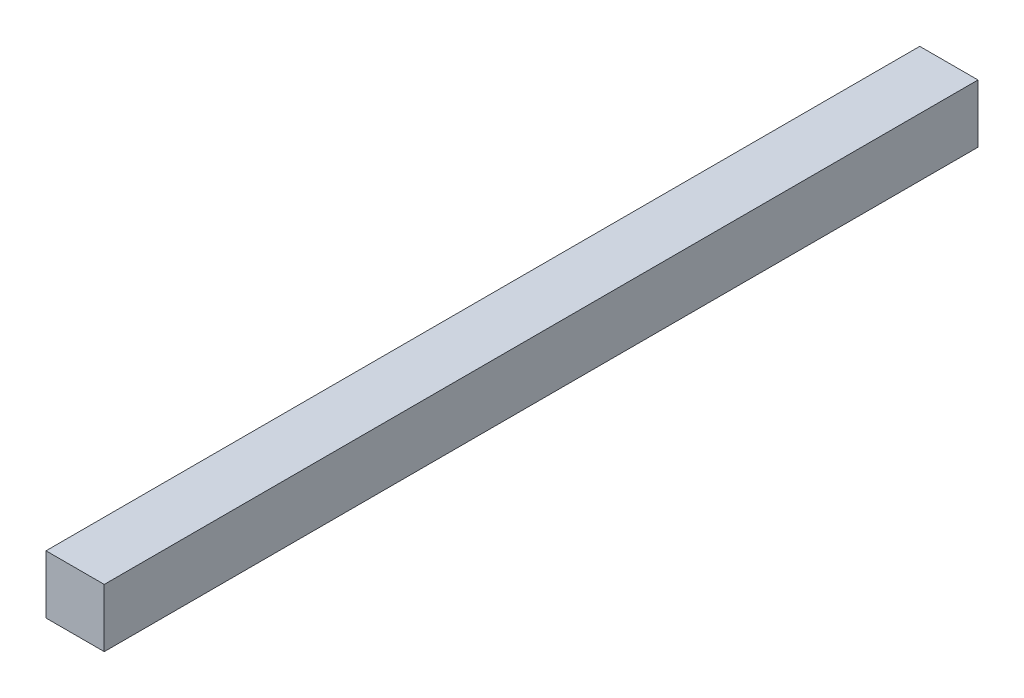
SolidWorks part; units mm, degrees
ref_plane "Płaszczyzna przednia" through (0, 0, 0) normal (0, 0, 1) x (1, 0, 0)
ref_plane "Płaszczyzna górna" through (0, 0, 0) normal (0, 1, 0) x (1, 0, 0)
ref_plane "Płaszczyzna prawa" through (0, 0, 0) normal (1, 0, 0) x (0, 0, -1)
sketch "Szkic1" plane through (0, 0, 0) normal (0, 0, 1) x (1, 0, 0)
  line L1 (-5, -5) -> (5, -5)
  line L2 (-5, -5) -> (-5, 5)
  line L3 (-5, 5) -> (5, 5)
  line L4 (5, -5) -> (5, 5)
  line L5 (-5, -5) -> (5, 5) construction
  line L6 (-5, 5) -> (5, -5) construction
  line L7 (-3.5, -3.5) -> (3.5, -3.5)
  line L8 (-3.5, -3.5) -> (-3.5, 3.5)
  line L9 (-3.5, 3.5) -> (3.5, 3.5)
  line L10 (3.5, -3.5) -> (3.5, 3.5)
  line L11 (-3.5, -3.5) -> (3.5, 3.5) construction
  line L12 (-3.5, 3.5) -> (3.5, -3.5) construction
  point P0 (0, 0)
  point P5 (0, 0)
  dimension "D1" = 10
  dimension "D2" = 7
extrude "Dodanie-wyciągnięcie1" add sketch "Szkic1" along normal blind 150 contours L1 L4 L3 L2 L10 L7 L8 L9
